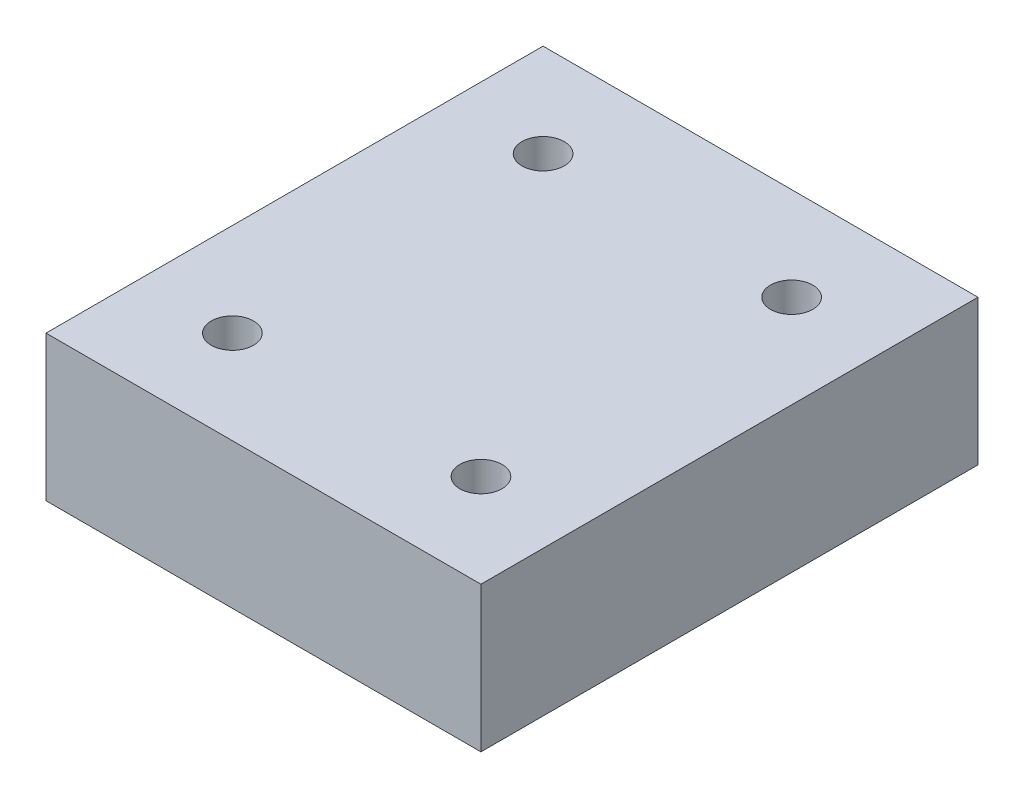
SolidWorks part; units mm, degrees
ref_plane "Front Plane" through (0, 0, 0) normal (0, 0, 1) x (1, 0, 0)
ref_plane "Top Plane" through (0, 0, 0) normal (0, 1, 0) x (1, 0, 0)
ref_plane "Right Plane" through (0, 0, 0) normal (1, 0, 0) x (0, 0, -1)
sketch "Sketch1" plane through (0, 0, 0) normal (0, 1, 0) x (1, 0, 0)
  line L1 (-17.5, -20) -> (17.5, -20)
  line L2 (-17.5, -20) -> (-17.5, 20)
  line L3 (-17.5, 20) -> (17.5, 20)
  line L4 (17.5, -20) -> (17.5, 20)
  line L5 (-17.5, -20) -> (17.5, 20) construction
  line L6 (-17.5, 20) -> (17.5, -20) construction
  point P0 (0, 0)
  dimension "D1" = 35
  dimension "D2" = 40
extrude "Boss-Extrude1" add sketch "Sketch1" along normal blind 11.6849
sketch "Sketch2" plane through (0, 11.6849, 0) normal (0, 1, 0) x (1, 0, 0)
  line L0 (0, 20) -> (0, 25.0488) construction
  line L1 (17.5, 20) -> (-17.5, 20) construction
  line L2 (0, -55) -> (0, 55) construction
  line L3 (-17.5, 20) -> (-17.5, -20) construction
  line L4 (-17.5, 0) -> (-23.153, 0) construction
  line L5 (-55, 0) -> (55, 0) construction
  circle A0 centre (-10, 12.5) radius 1.7
  circle A1 centre (10, 12.5) radius 1.7
  circle A2 centre (-10, -12.5) radius 1.7
  circle A3 centre (10, -12.5) radius 1.7
  dimension "D1" = 3.4
  dimension "D2" = 7.5
  dimension "D3" = 7.5
extrude "Cut-Extrude1" cut sketch "Sketch2" against normal up to surface (11.6849 mm away) up to face at (0, 0, 0)
equation "\"Force\"= 300"
equation "\"Safety Factor\"= 3"
equation "\"Safety Factor Froce\"= \"Force\" * \"Safety Factor\""
equation "\"Length\"= 40"
equation "\"Moment\"= \"Safety Factor Froce\" * \"Length\""
equation "\"Base\"= 35"
equation "\"Yield Strength\"= 45.2"
equation "\"Height\"= sqr ( ( 6 * \"Moment\" ) / ( \"Base\" * \"Yield Strength\" ) )"
equation "\"D1@Boss-Extrude1\"=\"Height\""
equation "\"D2@Sketch1\"=\"Length\""
equation "\"D1@Sketch1\"=\"Base\""
